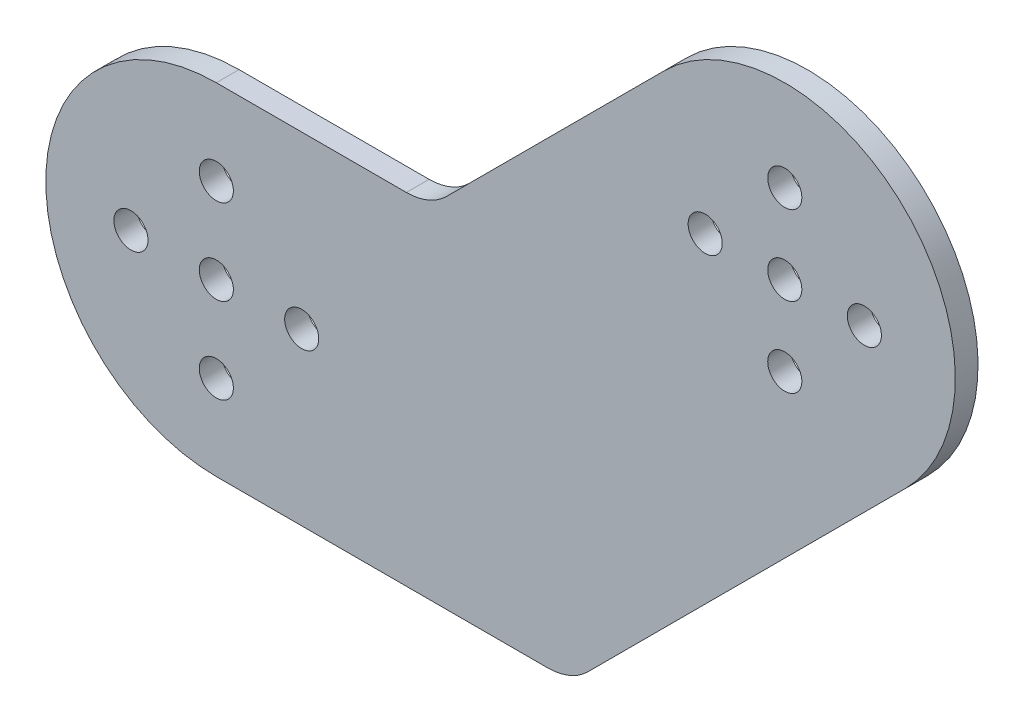
SolidWorks part; units mm, degrees
ref_plane "Alzado" through (0, 0, 0) normal (0, 0, 1) x (1, 0, 0)
ref_plane "Planta" through (0, 0, 0) normal (0, 1, 0) x (1, 0, 0)
ref_plane "Vista lateral" through (0, 0, 0) normal (1, 0, 0) x (0, 0, -1)
sketch "Croquis1" plane through (0, 0, 0) normal (0, 0, 1) x (1, 0, 0)
  circle A0 centre (0, 0) radius 1.5
  dimension "D1" = 3
sketch "Croquis2" plane through (0, 0, 0) normal (0, 0, 1) x (1, 0, 0)
  circle A0 centre (0, 7.5098) radius 1.5
sketch "Croquis3" plane through (0, 0, 0) normal (0, 0, 1) x (1, 0, 0)
  line L0 (0, 0) -> (50, 25) construction
  line L3 (0, 15) -> (16.7157, 15)
  line L4 (20.2513, 16.4645) -> (39.3934, 35.6066)
  line L6 (60.6066, 14.3934) -> (32.6777, -13.5355)
  line L8 (39.3934, 35.6066) -> (18.7868, 15) construction
  line L9 (29.1421, -15) -> (0, -15)
  line L10 (60.6066, 14.3934) -> (31.2132, -15) construction
  arc A0 (0, 15) -> (0, -15) centre (0, 0) ccw
  arc A1 (39.3934, 35.6066) -> (60.6066, 14.3934) centre (50, 25) cw
  arc A2 (16.7157, 15) -> (20.2513, 16.4645) centre (16.7157, 20) ccw
  arc A3 (32.6777, -13.5355) -> (29.1421, -15) centre (29.1421, -10) cw
  dimension "D1" = 5
  dimension "D2" = 5
extrude "Saliente-Extruir1" add sketch "Croquis3" along normal blind 2
extrude "Cortar-Extruir1" cut sketch "Croquis1" along normal blind 2 contours A0
extrude "Cortar-Extruir2" cut sketch "Croquis2" along normal blind 2 contours A0
pattern_circular "MatrizC1" count 4 over 360 about axis through (0, 0, 0) along (0, 0, 1) of "Cortar-Extruir2"
sketch "Croquis4" plane through (0, 0, 2) normal (0, 0, 1) x (1, 0, 0)
  circle A0 centre (50, 25) radius 1.5
  dimension "D1" = 3
extrude "Cortar-Extruir3" cut sketch "Croquis4" against normal blind 2
sketch "Croquis5" plane through (0, 0, 2) normal (0, 0, 1) x (1, 0, 0)
  circle A0 centre (50, 32) radius 1.5
extrude "Cortar-Extruir4" cut sketch "Croquis5" against normal blind 2
pattern_circular "MatrizC2" count 4 over 360 about axis through (50, 25, 0) along (0, 0, 1) of "Cortar-Extruir4"
